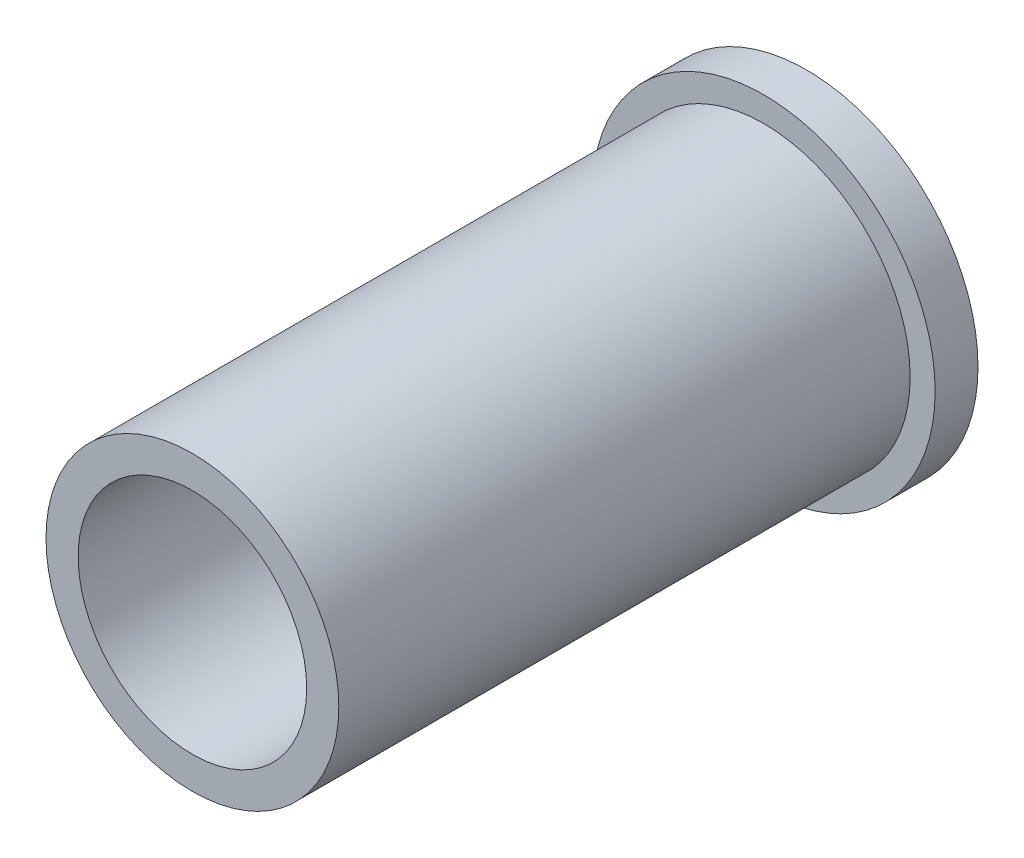
SolidWorks part; units mm, degrees
ref_plane "Front Plane" through (0, 0, 0) normal (0, 0, 1) x (1, 0, 0)
ref_plane "Top Plane" through (0, 0, 0) normal (0, 1, 0) x (1, 0, 0)
ref_plane "Right Plane" through (0, 0, 0) normal (1, 0, 0) x (0, 0, -1)
sketch "Sketch1" plane through (0, 0, 0) normal (0, 0, 1) x (1, 0, 0)
  circle A0 centre (0, 0) radius 8
  circle A1 centre (0, 0) radius 12
  dimension "D2" = 24
  dimension "D1" = 16
extrude "Boss-Extrude2" add sketch "Sketch1" along normal blind 3
sketch "Sketch2" plane through (0, 0, 3) normal (0, 0, 1) x (1, 0, 0)
  circle A0 centre (0, 0) radius 10.25
  circle A1 centre (0, 0) radius 8
  dimension "D1" = 20.5
  dimension "D2" = 16
extrude "Boss-Extrude3" add sketch "Sketch2" along normal blind 40
equation "\"shaft inner diameter\"= 15mm "
equation "\"shaft outer diameter\"= 20mm "
equation "\"keyway_height\" = 1.39mm "
equation "\"keyway_width\" = 2.78mm "
equation "\"keyway_length\" = 30mm "
equation "\"steering column length\" = 555mm "
equation "\"steering wheel bolt width\" = 6mm "
equation "\"steering wheel bolt length\" = 40mm "
equation "\"u_joint clearance\" = 30mm "
equation "\"u_joint thickness\" = 7.5mm "
equation "\"horizontal shaft length\" = 90mm "
equation "\"short_bearing_outer_width\" = 10mm "
equation "\"column bushing diameter\" = \"primary shaft small diameter\" + 4 "
equation "\"column bushing distance\" = \"steering column length\"/4 "
equation "\"pinion width\" = 26.5mm "
equation "\"number of teeth\" = 18mm "
equation "\"bushing length\" = 40mm "
equation "\"bushing thickness\" = 3mm "
equation "\"D1@Boss-Extrude3\"=\"bushing length\""
equation "\"D2@Sketch2\"=\"primary shaft small diameter\""
equation "\"D1@Boss-Extrude2\"=\"bushing thickness\""
equation "\"column angle\" = 45deg "
equation "\"D2@Sketch1\"=\"primary shaft large diameter\""
equation "\"D1@Sketch1\"=\"primary shaft small diameter\""
equation "\"wheel base\" = 1561mm "
equation "\"track\" = 1354mm "
equation "\"turning radius\" = 2000mm "
equation "\"turn to lock\" = 0.75mm "
equation "\"steering arm length\" = 100mm "
equation "\"primary shaft small diameter\" = 16mm "
equation "\"primary shaft large diameter\" = 24mm "
equation "\"secondary shaft small diameter\" = 16mm "
equation "\"secondary shaft large diameter\" = 25mm "
equation "\"pin hole diameter\" = 10mm "
equation "\"rack hole to hole\" = 500mm "
equation "\"rack length\" = \"rack hole to hole\" + \"pin hole diameter\"*2 "
equation "\"max turning angle\" = atn(\"wheel base\" / (\"turning radius\" - 0.5 * \"track\")) "
equation "\"max travel\" = 2 * \"steering arm length\" * sin(0.5 * \"max turning angle\") "
equation "\"pitch diameter\" = \"max travel\"/(pi * \"turn to lock\") "
equation "\"pressure angle\" = 20deg "
equation "\"module\" = \"pitch diameter\" / \"number of teeth\" "
equation "\"tie rod length\" = 305mm "
equation "\"tie rod inner diameter\" = 6.6mm "
equation "\"tie rod outer diameter\" = 8.1mm "
equation "\"D1@Sketch2\"=(\"secondary shaft large diameter\"+\"secondary shaft small diameter\")/2"
